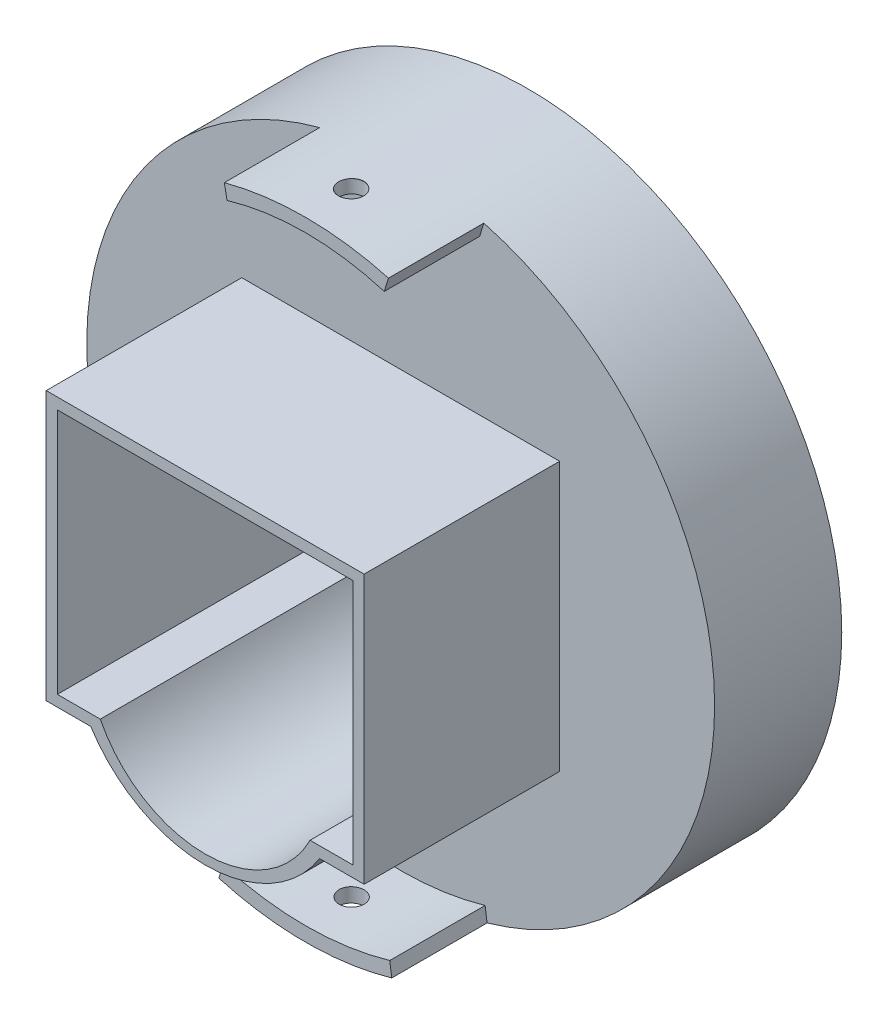
SolidWorks part; units mm, degrees
material "ABS"
ref_plane "Front Plane" through (0, 0, 0) normal (0, 0, 1) x (1, 0, 0)
ref_plane "Top Plane" through (0, 0, 0) normal (0, 1, 0) x (1, 0, 0)
ref_plane "Right Plane" through (0, 0, 0) normal (1, 0, 0) x (0, 0, -1)
sketch "Sketch1" plane through (0, 0, 0) normal (0, 0, 1) x (1, 0, 0)
  line L0 (16.764, -19.685) -> (23.622, -19.685)
  line L1 (-23.622, 19.685) -> (23.622, 19.685)
  line L2 (-23.622, 19.685) -> (-23.622, -19.685)
  line L3 (-23.622, -19.685) -> (-16.764, -19.685)
  line L4 (23.622, 19.685) -> (23.622, -19.685)
  line L5 (-23.622, 19.685) -> (23.622, -19.685) construction
  line L6 (-23.622, -19.685) -> (23.622, 19.685) construction
  circle A0 centre (0, 0) radius 50.165
  arc A1 (-16.764, -19.685) -> (16.764, -19.685) centre (0, -11.1845) ccw
  point P10 (0, 0)
  dimension "D1" = 100.33
  dimension "D5" = 18.796
  dimension "D2" = 47.244
  dimension "D3" = 39.37
  dimension "D4" = 6.858
extrude "Boss-Extrude1" add sketch "Sketch1" along normal blind 20.32
sketch "Sketch4" plane through (0, 0, 0) normal (0, 0, -1) x (-1, 0, 0)
  line L1 (-16.764, -19.685) -> (-23.622, -19.685)
  line L2 (-16.764, -19.685) -> (-16.764, 19.685)
  line L3 (-16.764, 19.685) -> (-23.622, 19.685)
  line L4 (-23.622, -19.685) -> (-23.622, 19.685)
  line L5 (16.764, -19.685) -> (23.622, -19.685)
  line L6 (16.764, -19.685) -> (16.764, 19.685)
  line L7 (16.764, 19.685) -> (23.622, 19.685)
  line L8 (23.622, -19.685) -> (23.622, 19.685)
extrude "Boss-Extrude3" add sketch "Sketch4" against normal blind 7.62
sketch "Sketch5" plane through (0, 0, 20.32) normal (0, 0, 1) x (1, 0, 0)
  line L0 (18.288, -21.463) -> (25.4, -21.463)
  line L1 (-25.4, -21.463) -> (-18.288, -21.463)
  line L2 (-25.4, -21.463) -> (-25.4, 21.463)
  line L3 (-25.4, 21.463) -> (25.4, 21.463)
  line L4 (25.4, -21.463) -> (25.4, 21.463)
  line L5 (-25.4, -21.463) -> (25.4, 21.463) construction
  line L6 (-25.4, 21.463) -> (25.4, -21.463) construction
  line L7 (-23.622, -19.685) -> (-16.764, -19.685)
  line L8 (-23.622, -19.685) -> (-23.622, 19.685)
  line L9 (-23.622, 19.685) -> (23.622, 19.685)
  line L10 (23.622, -19.685) -> (23.622, 19.685)
  line L11 (-23.622, -19.685) -> (23.622, 19.685) construction
  line L12 (-23.622, 19.685) -> (23.622, -19.685) construction
  line L14 (0, 0) -> (0, -31.496) construction
  line L15 (23.622, -19.685) -> (16.764, -19.685)
  arc A2 (-18.288, -21.463) -> (18.288, -21.463) centre (0, -9.812) ccw
  arc A4 (16.764, -19.685) -> (-16.764, -19.685) centre (0, -11.1845) cw
  point P0 (0, 0)
  point P6 (0, 0)
  dimension "D4" = 18.796
  dimension "D1" = 50.8
  dimension "D2" = 42.926
  dimension "D3" = 7.112
  dimension "D5" = 31.496
  dimension "D7" = 39.37
extrude "Boss-Extrude4" add sketch "Sketch5" along normal blind 31.242 contours L0 L4 L3 L2 L1
sketch "Sketch6" plane through (0, 0, 20.32) normal (0, 0, 1) x (1, 0, 0)
  line L2 (13.8091, -48.2269) -> (13.4945, -45.9627)
  line L3 (-13.8091, -48.2269) -> (-13.1798, -46.0292)
  line L4 (-12.9425, 48.4667) -> (-12.5071, 46.2225)
  line L5 (13.2937, 48.3715) -> (12.6118, 46.1896)
  circle A1 centre (0, 0) radius 50.165 construction
  arc A2 (-12.5071, 46.2225) -> (12.6118, 46.1896) centre (-0.0029, 4.0748) cw
  arc A3 (13.8091, -48.2269) -> (-13.8091, -48.2269) centre (0, 0) cw
  arc A4 (-13.1798, -46.0292) -> (13.4945, -45.9627) centre (0.0422, 0.1474) ccw
  arc A5 (-12.9425, 48.4667) -> (13.2937, 48.3715) centre (0, 0) cw
  point P17 (0, -50.165)
  dimension "D4" = 2.286
  dimension "D1" = 2.286
  dimension "D2" = 2.286
  dimension "D3" = 2.286
extrude "Boss-Extrude5" add sketch "Sketch6" along normal blind 15.24
hole_wizard "Ø4.0mm Dowel Hole1" positions "3DSketch1" profile "Sketch8" hole size "Ø4.0" standard "ANSI Metric"
sketch3d "3DSketch1"
  point P0 (-0.2913, 50.1642, 27.9451)
sketch "Sketch8" plane through (-0.2913, 50.1642, 27.9451) normal (0, 0, 1) x (-1, -0.0058, 0)
  line L0 (0, 0) -> (0, 5.0117)
  line L1 (0, 5.0117) -> (2, 3.81)
  line L2 (2, 3.81) -> (2, 0.021)
  line L3 (2, 0.021) -> (2.025, 0)
  line L5 (2.025, 0) -> (0, 0)
  line L6 (-2, 0.021) -> (-2.025, 0) construction
  line L10 (0, 5.0117) -> (-2, 3.81) construction
  line L11 (0, -6.35) -> (0, 107.95) construction
  dimension "Hole Dia." = 4
  dimension "Hole Depth" = 3.81
  dimension "Near C'Sink Dia." = 4.05
  dimension "Near C'Sink Angle" = 100
  dimension "Drill Angle" = 118
hole_wizard "Ø4.0mm Dowel Hole2" positions "3DSketch2" profile "Sketch9" hole size "Ø4.0" standard "ANSI Metric"
sketch3d "3DSketch2"
  point P0 (-0.2535, -50.1644, 27.9075)
sketch "Sketch9" plane through (-0.2535, -50.1644, 27.9075) normal (0, 0, 1) x (1, -0.0051, 0)
  line L0 (0, 0) -> (0, 5.0117)
  line L1 (0, 5.0117) -> (2, 3.81)
  line L2 (2, 3.81) -> (2, 0.021)
  line L3 (2, 0.021) -> (2.025, 0)
  line L5 (2.025, 0) -> (0, 0)
  line L6 (-2, 0.021) -> (-2.025, 0) construction
  line L10 (0, 5.0117) -> (-2, 3.81) construction
  line L11 (0, -6.35) -> (0, 107.95) construction
  dimension "Hole Dia." = 4
  dimension "Hole Depth" = 3.81
  dimension "Near C'Sink Dia." = 4.05
  dimension "Near C'Sink Angle" = 100
  dimension "Drill Angle" = 118
